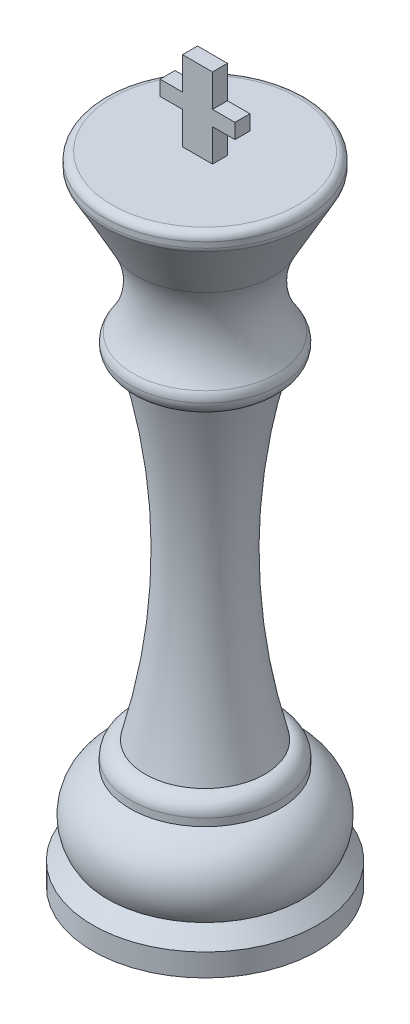
SolidWorks part; units mm, degrees
ref_plane "Front Plane" through (0, 0, 0) normal (0, 0, 1) x (1, 0, 0)
ref_plane "Top Plane" through (0, 0, 0) normal (0, 1, 0) x (1, 0, 0)
ref_plane "Right Plane" through (0, 0, 0) normal (1, 0, 0) x (0, 0, -1)
sketch "Sketch1" plane through (0, 0, 0) normal (0, 0, 1) x (1, 0, 0)
  line L0 (0, 0) -> (0, 108.0167) construction
  line L1 (0, 0) -> (-15, 0)
  line L2 (-15, 0) -> (-15, 3)
  line L3 (-15, 3) -> (-13, 5)
  line L4 (-10, 13.97) -> (-10, 14.97)
  line L5 (-9, 75.0658) -> (-13.3039, 82.8398)
  line L6 (-13.429, 83.3241) -> (-13.429, 85.0658)
  line L7 (-13.429, 85.0658) -> (0, 85.0658)
  line L8 (0, 85.0658) -> (0, 0)
  arc A0 (-13, 5) -> (-10, 13.97) centre (-7.9981, 8.3138) cw
  arc A1 (-10, 14.97) -> (-8, 16.97) centre (-8, 14.97) cw
  arc A2 (-8, 16.97) -> (-8, 60.99) centre (-90.1009, 38.98) ccw
  arc A3 (-8, 60.99) -> (-10, 62.99) centre (-8, 62.99) cw
  arc A4 (-10, 62.99) -> (-9.625, 64.15) centre (-8.0184, 62.99) cw
  arc A5 (-9.625, 64.15) -> (-9, 75.0658) centre (-17.8623, 70.0974) ccw
  arc A6 (-13.429, 83.3241) -> (-13.3039, 82.8398) centre (-12.429, 83.3241) ccw
  point P22 (-13.429, 83.0658)
  dimension "D7" = 6
  dimension "D9" = 2
  dimension "D13" = 85
  dimension "D14" = 2
  dimension "D19" = 10.16
  dimension "D23" = 1
  dimension "D1" = 30
  dimension "D2" = 3
  dimension "D3" = 2
  dimension "D4" = 26
  dimension "D5" = 20
  dimension "D6" = 8.97
  dimension "D8" = 1
  dimension "D10" = 16
  dimension "D11" = 44.02
  dimension "D12" = 16
  dimension "D15" = 20
  dimension "D16" = 3.16
  dimension "D17" = 19.25
  dimension "D18" = 18
  dimension "D20" = 8
  dimension "D21" = 28.97
  dimension "D22" = 2
revolve "Revolve1" add sketch "Sketch1" angle 360 about L0
fillet "Fillet1" radius 1 1 edges at (0, 85.0658, -13.429)
sketch "Sketch2" plane through (0, 0, 0) normal (0, 0, 1) x (1, 0, 0)
  line L1 (-2.009, 85.0658) -> (1.991, 85.0658)
  line L6 (12.429, 85.0658) -> (-12.429, 85.0658) construction
  line L7 (1.991, 85.0658) -> (1.991, 89.402)
  line L8 (1.991, 89.402) -> (4.991, 89.402)
  line L9 (4.991, 89.402) -> (4.991, 91.402)
  line L10 (4.991, 91.402) -> (1.991, 91.402)
  line L11 (1.991, 91.402) -> (1.991, 95.7383)
  line L12 (1.991, 95.7383) -> (-2.009, 95.7383)
  line L13 (-2.009, 95.7383) -> (-2.009, 91.402)
  line L14 (-2.009, 91.402) -> (-5.009, 91.402)
  line L15 (-5.009, 91.402) -> (-5.009, 89.402)
  line L16 (-5.009, 89.402) -> (-2.009, 89.402)
  line L17 (-2.009, 89.402) -> (-2.009, 85.0658)
  point P5 (-0.009, 85.0658)
  point P15 (-3.509, 91.402)
  dimension "D1" = 2
  dimension "D2" = 2
  dimension "D3" = 4
  dimension "D4" = 4
  dimension "D5" = 10
  dimension "D6" = 10.42
  dimension "D7" = 10.6725
extrude "Boss-Extrude1" add sketch "Sketch2" along normal mid plane 2
